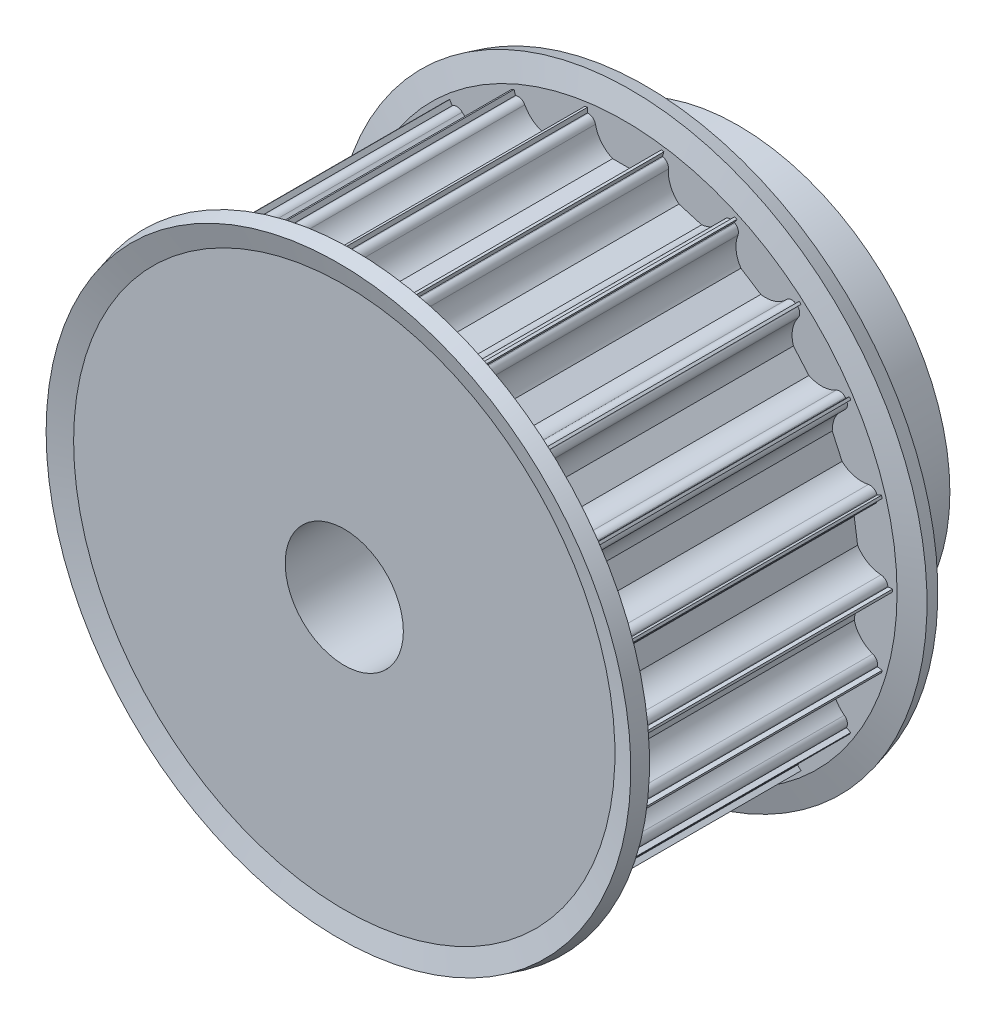
SolidWorks part; units mm, degrees
ref_plane "Front Plane" through (0, 0, 0) normal (0, 0, 1) x (1, 0, 0)
ref_plane "Top Plane" through (0, 0, 0) normal (0, 1, 0) x (1, 0, 0)
ref_plane "Right Plane" through (0, 0, 0) normal (1, 0, 0) x (0, 0, -1)
sketch "Sketch1" plane through (0, 0, 0) normal (1, 0, 0) x (0, 0, -1)
  line L0 (0, 0) -> (25.3151, 0) construction
  line L1 (0, 6) -> (40, 6)
  line L2 (40, 6) -> (40, 21.5)
  line L3 (40, 21.5) -> (30, 21.5)
  line L4 (30, 21.5) -> (30, 27.25)
  line L5 (30, 27.25) -> (0, 27.25)
  line L6 (0, 27.25) -> (0, 6)
  dimension "D1" = 6
  dimension "D2" = 27.25
  dimension "D3" = 30
  dimension "D4" = 15.5
  dimension "D5" = 40
  dimension "D6" = 10
revolve "Revolve1" add sketch "Sketch1" angle 360 about L0
sketch "Sketch5" plane through (0, 0, 0) normal (0, 0, 1) x (1, 0, 0)
  line L0 (-3.6742, 26.5) -> (-3.75, 26.5)
  line L1 (-3.75, 26.5) -> (-3.75, 28.5)
  line L2 (-3.75, 28.5) -> (3.75, 28.5)
  line L3 (3.75, 28.5) -> (3.75, 26.5)
  line L4 (3.75, 26.5) -> (3.6742, 26.5)
  line L6 (1.199, 23.75) -> (-1.199, 23.75)
  arc A0 (-2.9394, 25.9) -> (-1.199, 23.75) centre (0, 26.5) ccw
  arc A1 (-2.9394, 25.9) -> (-3.6742, 26.5) centre (-3.6742, 25.75) ccw
  arc A2 (2.9394, 25.9) -> (3.6742, 26.5) centre (3.6742, 25.75) cw
  arc A3 (1.199, 23.75) -> (2.9394, 25.9) centre (0, 26.5) ccw
  point P3 (0, 28.5)
  point P11 (-3, 26.5)
  point P14 (3, 26.5)
  dimension "D1" = 3
  dimension "D5" = 0.75
  dimension "D6" = 0.75
  dimension "D2" = 26.5
  dimension "D3" = 7.5
  dimension "D4" = 2
  dimension "D7" = 2.75
extrude "Cut-Extrude1" cut sketch "Sketch5" against normal up to next
pattern_circular "CirPattern1" count 22 over 360 about axis through (0, 0, 0) along (0, 0, 1) of "Cut-Extrude1"
sketch "Sketch6" plane through (0, 0, 0) normal (1, 0, 0) x (0, 0, -1)
  line L0 (15, 26.9539) -> (15, 8.7755) construction
  line L1 (30, 26.9539) -> (0, 26.9539) construction
  line L2 (30, 8.7755) -> (0, 8.7755) construction
  line L3 (30, 21.5) -> (30, 27.4856)
  line L4 (30, 27.4856) -> (30.5902, 29.6881)
  line L5 (30.5902, 29.6881) -> (29.0902, 30.09)
  line L6 (29.0902, 30.09) -> (28.4471, 27.69)
  line L7 (28.4471, 27.69) -> (28.4471, 21.5)
  line L8 (28.4471, 21.5) -> (30, 21.5)
  line L10 (40, 21.5) -> (30, 21.5) construction
  line L11 (1.5529, 21.5) -> (0, 21.5)
  line L12 (1.5529, 27.69) -> (1.5529, 21.5)
  line L13 (0, 21.5) -> (0, 27.4856)
  line L14 (0, 27.4856) -> (-0.5902, 29.6881)
  line L15 (-0.5902, 29.6881) -> (0.9098, 30.09)
  line L16 (0.9098, 30.09) -> (1.5529, 27.69)
  line L17 (0, 0) -> (-21.568, 0) construction
  dimension "D1" = 15
  dimension "D2" = 1.5
  dimension "D3" = 6.19
  dimension "D4" = 2.4
revolve "Revolve2" add sketch "Sketch6" angle 360 about L17
